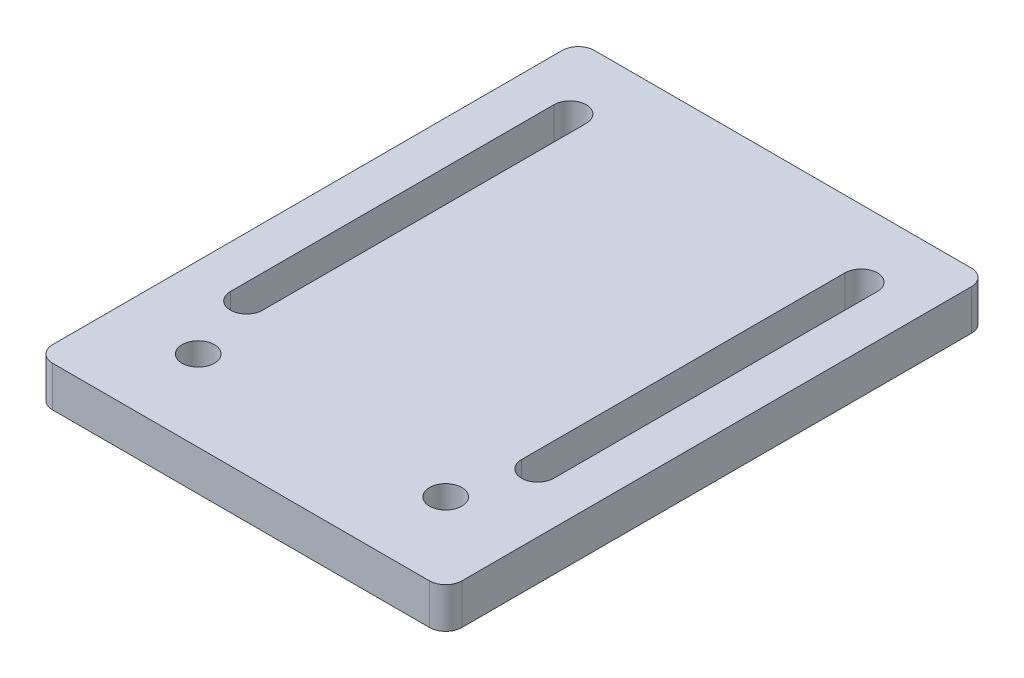
SolidWorks part; units mm, degrees
ref_plane "前视基准面" through (0, 0, 0) normal (0, 0, 1) x (1, 0, 0)
ref_plane "上视基准面" through (0, 0, 0) normal (0, 1, 0) x (1, 0, 0)
ref_plane "右视基准面" through (0, 0, 0) normal (1, 0, 0) x (0, 0, -1)
other "Configuration Table"
sketch "草图1" plane through (0, 0, 0) normal (0, 1, 0) x (1, 0, 0)
  line L0 (0, 13.6232) -> (0, -16.4238) construction
  line L1 (-15.3, 0) -> (-15.3, -40) construction
  line L4 (25.3, 17) -> (-25.3, 17)
  line L5 (-25.3, 17) -> (-25.3, -50)
  line L6 (-25.3, -50) -> (0.6311, -50)
  line L7 (25.3, -50) -> (-0.6311, -50)
  line L8 (25.3, 17) -> (25.3, -50)
  line L9 (15.3, 0) -> (15.3, -40) construction
  arc A2 (-17.3, -40) -> (-13.3, -40) centre (-15.3, -40) ccw
  arc A4 (17.3, -40) -> (13.3, -40) centre (15.3, -40) cw
  circle A5 centre (-15.3, -40) radius 2
  circle A6 centre (15.3, -40) radius 2
  point P5 (-15.3, -20)
  point P17 (0, 17)
  point P19 (15.3, -20)
  dimension "D1" = 67
  dimension "D2" = 15.3
  dimension "D6" = 10
extrude "凸台-拉伸1" add sketch "草图1" along normal blind 5
fillet "圆角1" radius 2 4 edges at (-25.3, 2.5, -17) (25.3, 2.5, -17) (25.3, 2.5, 50) (-25.3, 2.5, 50)
sketch "草图2" plane through (0, 5, 0) normal (0, 1, 0) x (1, 0, 0)
  line L0 (0, 14.3099) -> (0, -58.1803) construction
  line L1 (18, 8.6789) -> (18, -31.3211) construction
  line L2 (20, 8.6789) -> (20, -31.3211)
  line L3 (16, 8.6789) -> (16, -31.3211)
  line L4 (-18, 8.6789) -> (-18, -31.3211) construction
  line L5 (-20, 8.6789) -> (-20, -31.3211)
  line L6 (-16, 8.6789) -> (-16, -31.3211)
  arc A1 (20, 8.6789) -> (16, 8.6789) centre (18, 8.6789) ccw
  arc A2 (16, -31.3211) -> (20, -31.3211) centre (18, -31.3211) ccw
  arc A3 (-20, 8.6789) -> (-16, 8.6789) centre (-18, 8.6789) cw
  arc A4 (-16, -31.3211) -> (-20, -31.3211) centre (-18, -31.3211) cw
  point P5 (18, -11.3211)
  point P12 (-18, -11.3211)
  dimension "D1" = 4
  dimension "D2" = 18
  dimension "D3" = 40
extrude "切除-拉伸1" cut sketch "草图2" against normal through all both and the other way through all
